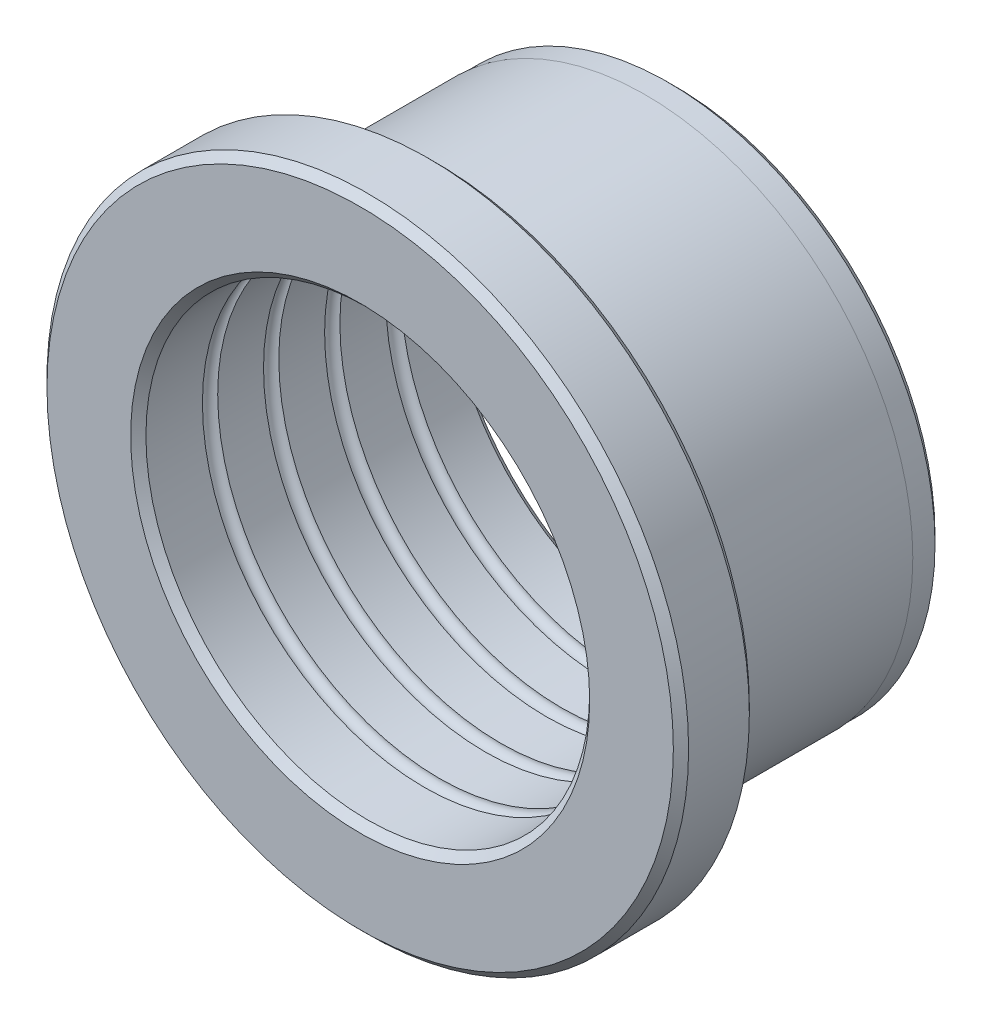
SolidWorks part; units mm, degrees
material "PB01 (C90710) Bronze"
ref_plane "Front" through (0, 0, 0) normal (0, 0, 1) x (1, 0, 0)
ref_plane "Top" through (0, 0, 0) normal (0, 1, 0) x (1, 0, 0)
ref_plane "Right" through (0, 0, 0) normal (1, 0, 0) x (0, 0, -1)
sketch "Sketch1" plane through (0, 0, 0) normal (1, 0, 0) x (0, 0, -1)
  line L0 (0, 0) -> (20.675, 0) construction
  line L1 (0.5, 14.5275) -> (4.2, 14.5275)
  line L2 (20.675, 15.0275) -> (20.675, 16.9625)
  line L3 (18.675, 17.5075) -> (5.375, 17.5075)
  line L4 (4.975, 17.9075) -> (4.975, 20.505)
  line L5 (4.475, 21.005) -> (0.5, 21.005)
  line L6 (0, 20.505) -> (0, 15.0275)
  line L7 (20.175, 17.4625) -> (18.675, 17.4625)
  line L8 (18.675, 17.4625) -> (18.675, 17.5075)
  line L9 (5.2, 14.5275) -> (8.2, 14.5275)
  line L10 (9.2, 14.5275) -> (12.2, 14.5275)
  line L11 (13.2, 14.5275) -> (16.2, 14.5275)
  line L12 (17.2, 14.5275) -> (20.175, 14.5275)
  line L13 (0, 15.0275) -> (0.5, 14.5275)
  line L14 (20.175, 14.5275) -> (20.675, 15.0275)
  line L15 (20.675, 16.9625) -> (20.175, 17.4625)
  line L16 (4.975, 20.505) -> (4.475, 21.005)
  line L17 (0.5, 21.005) -> (0, 20.505)
  arc A0 (4.2, 14.5275) -> (5.2, 14.5275) centre (4.7, 14.525) cw
  arc A1 (8.2, 14.5275) -> (9.2, 14.5275) centre (8.7, 14.525) cw
  arc A2 (12.2, 14.5275) -> (13.2, 14.5275) centre (12.7, 14.525) cw
  arc A3 (16.2, 14.5275) -> (17.2, 14.5275) centre (16.7, 14.525) cw
  arc A4 (5.375, 17.5075) -> (4.975, 17.9075) centre (5.375, 17.9075) cw
  point P3 (0, 22.5)
  point P4 (-17.5682, 22.5)
  point P5 (-12.7682, 22.5)
  point P6 (-12.7682, 0)
  point P7 (0, 17.5)
  point P8 (0, 14.5275)
  point P9 (-20.8, 17.5)
  point P10 (20.675, 14.5275)
  point P11 (4.975, 21.005)
  point P15 (0, 21.005)
  point P16 (20.675, 17.4625)
  dimension "D2" = 29.055
  dimension "D8" = 0.5
  dimension "D9" = 30.05
  dimension "D12" = 0.5
  dimension "D13" = 0.5
  dimension "D14" = 0.5
  dimension "D16" = 0.4
  dimension "D1" = 20.675
  dimension "D3" = 2
  dimension "D4" = 34.925
  dimension "D5" = 35.015
  dimension "D6" = 42.01
  dimension "D7" = 4.975
  dimension "D10" = 4.7
  dimension "D11" = 4
  dimension "D15" = 4
revolve "Revolve1" add sketch "Sketch1" angle 360 about L0
